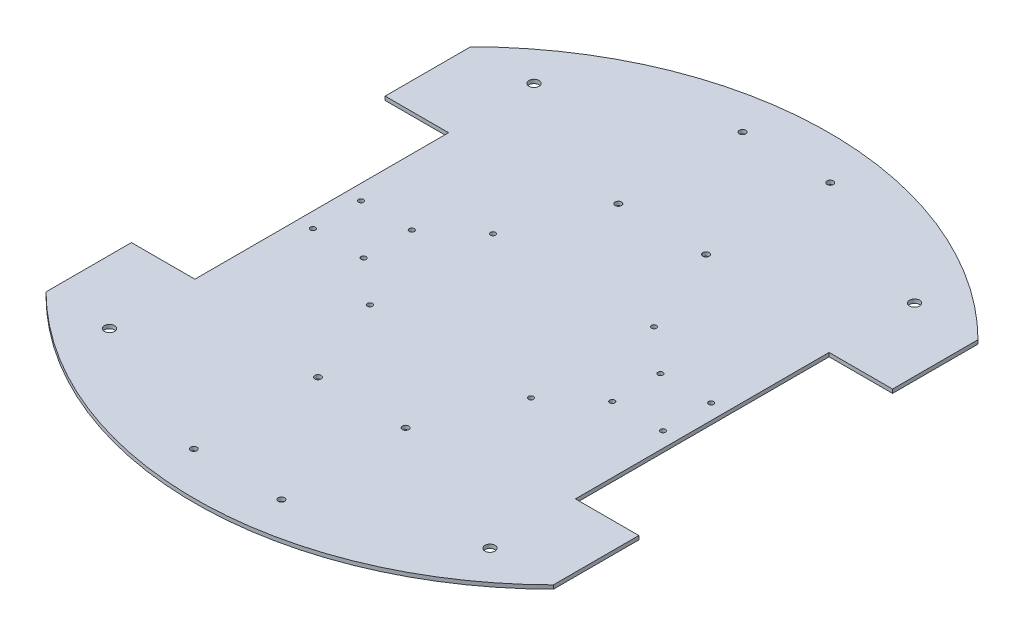
SolidWorks part; units mm, degrees
ref_plane "Front Plane" through (0, 0, 0) normal (0, 0, 1) x (1, 0, 0)
ref_plane "Top Plane" through (0, 0, 0) normal (0, 1, 0) x (1, 0, 0)
ref_plane "Right Plane" through (0, 0, 0) normal (1, 0, 0) x (0, 0, -1)
sketch "Sketch2" plane through (0, 0, 0) normal (0, 1, 0) x (1, 0, 0)
  line L0 (2.8162, -115.0735) -> (52.8162, -115.0735)
  line L6 (352.8162, -115.0735) -> (402.8162, -115.0735)
  line L8 (2.8162, -315.0735) -> (52.8162, -315.0735)
  line L9 (52.8162, -115.0735) -> (52.8162, -315.0735)
  line L10 (352.8162, -315.0735) -> (402.8162, -315.0735)
  line L11 (352.8162, -115.0735) -> (352.8162, -315.0735)
  line L12 (402.8162, -315.0735) -> (402.8162, -382.4334)
  line L13 (2.8162, -115.0735) -> (2.8162, -47.7135)
  line L14 (402.8162, -47.7135) -> (402.8162, -115.0735)
  line L15 (2.8162, -315.0735) -> (2.8162, -382.4334)
  arc A0 (402.8162, -382.4334) -> (2.8162, -382.4334) centre (202.8162, -181.7401) cw
  arc A1 (2.8162, -47.7135) -> (402.8162, -47.7135) centre (202.8162, -248.4068) cw
extrude "Boss-Extrude1" add sketch "Sketch2" along normal blind 3
ref_plane "Plane1" through (202.8162, 0, 0) normal (1, 0, 0) x (0, 0, -1)
sketch "Sketch3" plane through (0, 3, 0) normal (0, 1, 0) x (1, 0, 0)
  line L0 (278.3568, -215.0735) -> (-172.7244, -215.0735) construction
  line L1 (202.8162, 34.9265) -> (202.8162, -465.0735) construction
  line L2 (52.8162, -115.0735) -> (52.8162, -315.0735) construction
  line L3 (52.8162, -188.5735) -> (52.8162, -178.5735) construction
  line L4 (352.8162, -188.5735) -> (352.8162, -178.5735) construction
  circle A0 centre (64.8162, -196.0735) radius 2
  circle A4 centre (104.8162, -196.0735) radius 2
  circle A5 centre (104.8162, -234.0735) radius 2
  circle A6 centre (64.8162, -234.0735) radius 2
  arc A11 (402.8162, -47.7135) -> (2.8162, -47.7135) centre (202.8162, -248.4068) ccw construction
  arc A12 (2.8162, -382.4334) -> (402.8162, -382.4334) centre (202.8162, -181.7401) ccw construction
  circle A13 centre (340.8162, -234.0735) radius 2
  circle A14 centre (300.8162, -234.0735) radius 2
  circle A15 centre (300.8162, -196.0735) radius 2
  circle A16 centre (340.8162, -196.0735) radius 2
  point P3 (52.8162, -215.0735)
  point P24 (52.8162, -215.0735)
  point P34 (352.8162, -215.0735)
  dimension "D1" = 12
  dimension "D2" = 19
  dimension "D3" = 40
  dimension "D5" = 38
  dimension "D6" = 4
  dimension "D7" = 4
  dimension "D4" = 500
ref_plane "Plane2" through (202.8162, 0, 0) normal (-1, 0, 0) x (0, 0, 1)
extrude "Cut-Extrude5" cut sketch "Sketch3" against normal blind 10
sketch "Sketch4" plane through (0, 3, 0) normal (0, 1, 0) x (1, 0, 0)
  line L0 (202.8162, 34.9265) -> (202.8162, -465.0735) construction
  line L1 (52.8162, -215.0735) -> (352.8162, -215.0735) construction
  line L2 (52.8162, -115.0735) -> (52.8162, -315.0735) construction
  line L3 (352.8162, -315.0735) -> (352.8162, -115.0735) construction
  circle A0 centre (52.8162, -47.7135) radius 4
  arc A1 (402.8162, -47.7135) -> (2.8162, -47.7135) centre (202.8162, -248.4068) ccw construction
  arc A2 (2.8162, -382.4334) -> (402.8162, -382.4334) centre (202.8162, -181.7401) ccw construction
  circle A3 centre (352.8162, -47.7135) radius 4
  circle A4 centre (352.8162, -382.4334) radius 4
  circle A5 centre (52.8162, -382.4334) radius 4
extrude "Cut-Extrude6" cut sketch "Sketch4" against normal blind 10
sketch "Sketch6" plane through (0, 3, 0) normal (0, 1, 0) x (1, 0, 0)
  line L0 (131.3162, -158.5735) -> (139.3162, -158.5735)
  line L1 (274.3162, -158.5735) -> (131.3162, -158.5735)
  line L2 (274.3162, -158.5735) -> (274.3162, -271.5735)
  line L3 (274.3162, -271.5735) -> (131.3162, -271.5735)
  line L4 (131.3162, -158.5735) -> (131.3162, -271.5735)
  line L8 (202.8162, -158.5735) -> (202.8162, -271.5735) construction
  line L9 (131.3162, -215.0735) -> (274.3162, -215.0735) construction
  circle A0 centre (139.3162, -166.5735) radius 2
  circle A1 centre (266.3162, -166.5735) radius 2
  circle A2 centre (266.3162, -263.5735) radius 2
  circle A3 centre (139.3162, -263.5735) radius 2
  point P0 (202.8162, -215.0735)
extrude "Cut-Extrude7" cut sketch "Sketch6" against normal blind 10 contours A3 | A0 | A1 | A2
sketch "Sketch7" plane through (0, 3, 0) normal (0, 1, 0) x (1, 0, 0)
  line L0 (52.8162, -215.0735) -> (52.8162, -188.5735)
  line L1 (52.8162, -115.0735) -> (52.8162, -315.0735) construction
sketch "Sketch8" plane through (0, 3, 0) normal (0, 1, 0) x (1, 0, 0)
  line L0 (52.8162, -215.0735) -> (352.8162, -215.0735) construction
  line L5 (352.8162, -315.0735) -> (352.8162, -115.0735) construction
  circle A0 centre (168.2562, -333.4734) radius 2.5
  circle A1 centre (237.3762, -333.4734) radius 2.5
  circle A2 centre (237.3762, -431.3934) radius 2.5
  circle A3 centre (168.2562, -431.3934) radius 2.5
  circle A4 centre (168.2562, 1.2465) radius 2.5
  circle A5 centre (237.3762, 1.2465) radius 2.5
  circle A6 centre (237.3762, -96.6735) radius 2.5
  circle A7 centre (168.2562, -96.6735) radius 2.5
  dimension "D1" = 97.92
  dimension "D2" = 69.12
extrude "Cut-Extrude8" cut sketch "Sketch8" against normal blind 55
